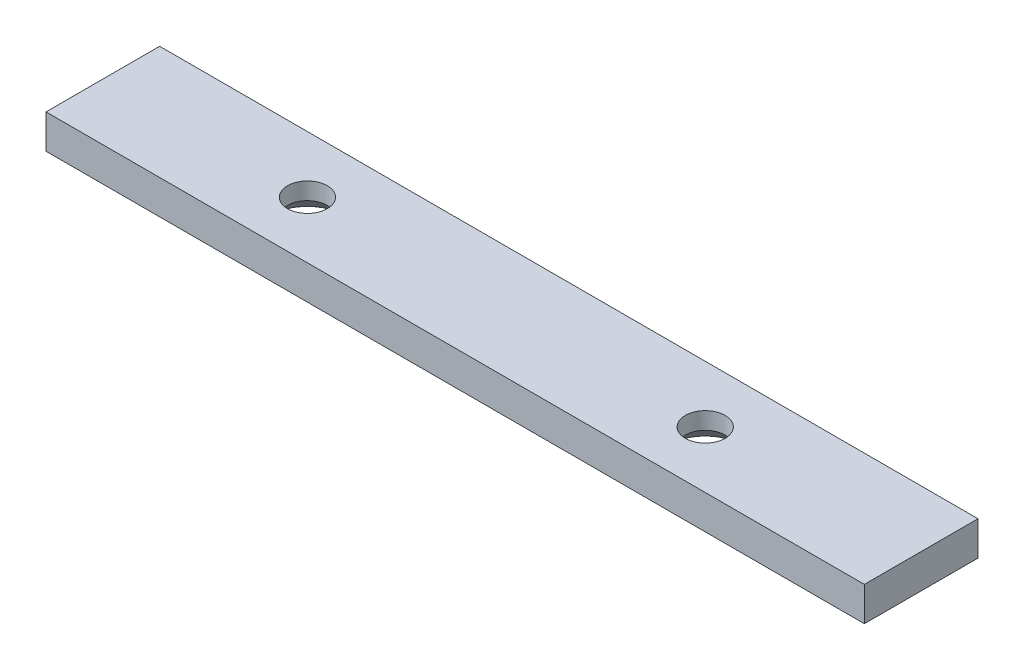
SolidWorks part; units mm, degrees
ref_plane "Front Plane" through (0, 0, 0) normal (0, 0, 1) x (1, 0, 0)
ref_plane "Top Plane" through (0, 0, 0) normal (0, 1, 0) x (1, 0, 0)
ref_plane "Right Plane" through (0, 0, 0) normal (1, 0, 0) x (0, 0, -1)
sketch "Sketch1" plane through (0, 0, 0) normal (0, 1, 0) x (1, 0, 0)
  line L1 (-72, 10) -> (72, 10)
  line L2 (-72, 10) -> (-72, -10)
  line L3 (-72, -10) -> (72, -10)
  line L4 (72, 10) -> (72, -10)
  line L5 (-72, 10) -> (72, -10) construction
  line L6 (-72, -10) -> (72, 10) construction
  point P0 (0, 0)
extrude "Boss-Extrude1" add sketch "Sketch1" along normal blind 6
hole_wizard "CSK for M1.6 Countersunk Flat Head Screw1" positions "3DSketch1" profile "Sketch3" countersink size "M1.6" standard "ISO" end condition up to next
sketch3d "3DSketch1"
  line L1 (72, 0, 10) -> (72, 0, -10) construction
  point P0 (34, 0, 0)
  dimension "D1" = 38
sketch "Sketch3" plane through (34, 0, 0) normal (1, 0, 0) x (0, 0, -1)
  line L0 (0, 0) -> (0, 6)
  line L1 (0, 6) -> (3.5, 6)
  line L2 (3.5, 6) -> (3.5, 3)
  line L3 (3.5, 3) -> (6.5, 0)
  line L5 (6.5, 0) -> (0, 0)
  line L6 (-3.5, 3) -> (-6.5, 0) construction
  line L11 (0, -6.35) -> (0, 107.95) construction
  dimension "Thru Hole Dia." = 7
  dimension "Thru Hole Depth" = 6
  dimension "Near C'Sink Dia." = 13
  dimension "Near C'Sink Angle" = 90
pattern_linear "LPattern1" count 2 spacing 70 along (-1, 0, 0) of "CSK for M1.6 Countersunk Flat Head Screw1"
